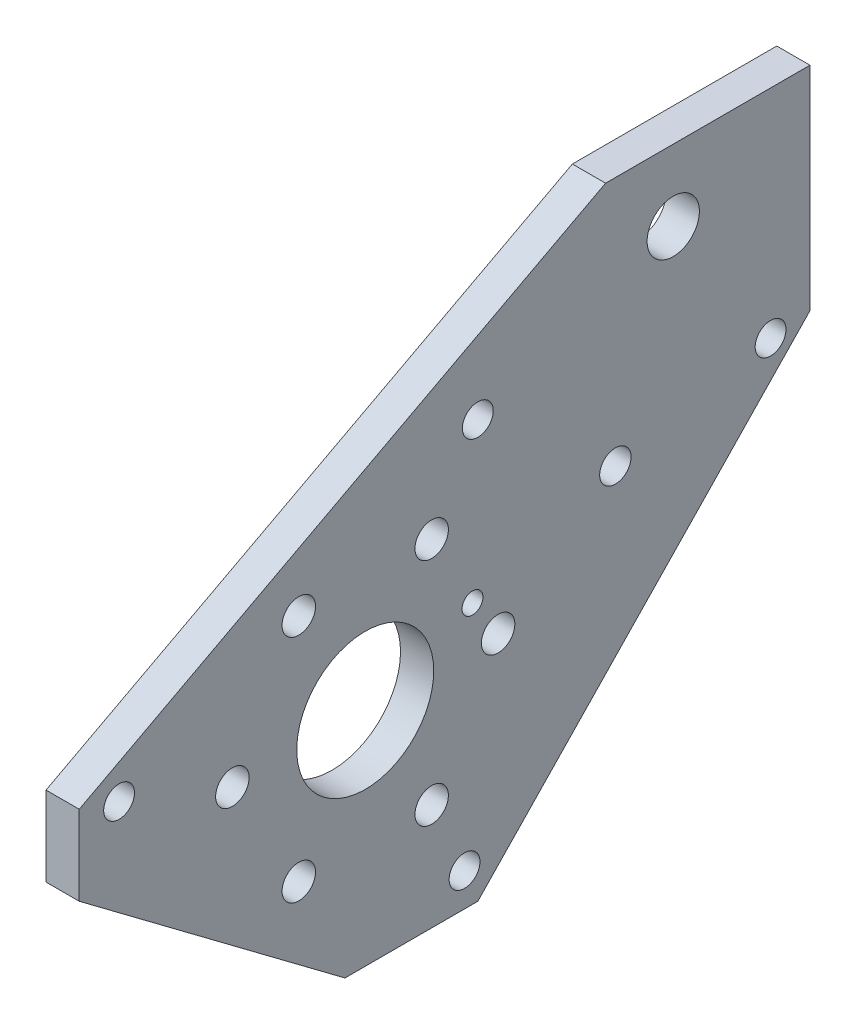
SolidWorks part; units mm, degrees
ref_plane "Front Plane" through (0, 0, 0) normal (0, 0, 1) x (1, 0, 0)
ref_plane "Top Plane" through (0, 0, 0) normal (0, 1, 0) x (1, 0, 0)
ref_plane "Right Plane" through (0, 0, 0) normal (1, 0, 0) x (0, 0, -1)
sketch "Sketch1" plane through (0, 0, 0) normal (1, 0, 0) x (0, 0, -1)
  line L1 (0, 0) -> (69.85, 0)
  line L2 (0, 0) -> (0, 53.34)
  line L3 (0, 53.34) -> (69.85, 53.34)
  line L4 (69.85, 0) -> (69.85, 53.34)
  dimension "D1" = 53.34
  dimension "D2" = 69.85
extrude "Boss-Extrude1" add sketch "Sketch1" along normal blind 3.175
hole_wizard "1/2 Clearance Hole1" positions "Sketch3" profile "Sketch2" hole size "1/2" standard "ANSI Inch"
sketch "Sketch3" plane through (3.175, 0, 0) normal (1, 0, 0) x (0, 0, -1)
  line L0 (0, 0) -> (69.85, 0) construction
  line L1 (0, 53.34) -> (0, 0) construction
  point P0 (27.3378, 21.1869)
  point P3 (34.925, 0)
  dimension "D1" = 21.1869
  dimension "D2" = 27.3378
sketch "Sketch2" plane through (3.175, 21.1869, -27.3378) normal (0, 1, 0) x (0, 0, -1)
  line L0 (0, 0) -> (0, 29.3345)
  line L1 (0, 29.3345) -> (6.5481, 25.4)
  line L2 (6.5481, 25.4) -> (6.5481, 0)
  line L5 (6.5481, 0) -> (0, 0)
  line L10 (0, 29.3345) -> (-6.5481, 25.4) construction
  line L11 (0, -6.35) -> (0, 107.95) construction
  dimension "Hole Dia." = 13.0962
  dimension "Hole Depth" = 25.4
  dimension "Drill Angle" = 118
hole_wizard "M3 Clearance Hole1" positions "Sketch5" profile "Sketch4" hole size "M3" standard "ANSI Metric"
sketch "Sketch5" plane through (0, 0, 0) normal (-1, 0, 0) x (0, 0, 1)
  line L11 (-27.3378, 21.1869) -> (-40.0378, 21.1869) construction
  line L12 (-27.3378, 21.1869) -> (-33.6878, 32.1855) construction
  line L13 (-27.3378, 21.1869) -> (-20.9878, 32.1855) construction
  line L14 (-27.3378, 21.1869) -> (-14.6378, 21.1869) construction
  line L15 (-27.3378, 21.1869) -> (-20.9878, 10.1884) construction
  line L16 (-27.3378, 21.1869) -> (-33.6878, 10.1884) construction
  point P55 (-40.0378, 21.1869)
  point P66 (-33.6878, 32.1855)
  point P67 (-20.9878, 32.1855)
  point P68 (-14.6378, 21.1869)
  point P69 (-20.9878, 10.1884)
  point P70 (-33.6878, 10.1884)
  point P71 (-27.3378, 21.1869)
  dimension "D1" = 12.7
  dimension "D2" = 6
sketch "Sketch4" plane through (0, 21.1869, -40.0378) normal (0, 1, 0) x (0, 0, 1)
  line L0 (0, 0) -> (0, 26.3614)
  line L1 (0, 26.3614) -> (1.6, 25.4)
  line L2 (1.6, 25.4) -> (1.6, 0)
  line L5 (1.6, 0) -> (0, 0)
  line L10 (0, 26.3614) -> (-1.6, 25.4) construction
  line L11 (0, -6.35) -> (0, 107.95) construction
  dimension "Hole Dia." = 3.2
  dimension "Hole Depth" = 25.4
  dimension "Drill Angle" = 118
hole_wizard "Ø2.0mm Clearance Dowel Hole1" positions "Sketch7" profile "Sketch6" hole size "Ø2.0" standard "ANSI Metric"
sketch "Sketch7" plane through (3.175, 0, 0) normal (1, 0, 0) x (0, 0, -1)
  line L0 (0, 53.34) -> (0, 0) construction
  line L1 (0, 0) -> (69.85, 0) construction
  point P0 (37.5906, 24.9513)
  dimension "D1" = 37.5906
  dimension "D2" = 24.9513
sketch "Sketch6" plane through (3.175, 24.9513, -37.5906) normal (0, 1, 0) x (0, 0, -1)
  line L0 (0, 0) -> (0, 26.0009)
  line L1 (0, 26.0009) -> (1, 25.4)
  line L2 (1, 25.4) -> (1, 0)
  line L5 (1, 0) -> (0, 0)
  line L10 (0, 26.0009) -> (-1, 25.4) construction
  line L11 (0, -6.35) -> (0, 107.95) construction
  dimension "Hole Dia." = 2
  dimension "Hole Depth" = 25.4
  dimension "Drill Angle" = 118
hole_wizard "Ø3.0mm Clearance Dowel Hole1" positions "Sketch9" profile "Sketch8" hole size "Ø3.0" standard "ANSI Metric"
sketch "Sketch9" plane through (3.175, 0, 0) normal (1, 0, 0) x (0, 0, -1)
  line L0 (0, 53.34) -> (0, 0) construction
  line L1 (0, 0) -> (69.85, 0) construction
  point P0 (51.2475, 29.4626)
  dimension "D1" = 51.2475
  dimension "D2" = 29.4626
sketch "Sketch8" plane through (3.175, 29.4626, -51.2475) normal (0, 1, 0) x (0, 0, -1)
  line L0 (0, 0) -> (0, 26.3013)
  line L1 (0, 26.3013) -> (1.5, 25.4)
  line L2 (1.5, 25.4) -> (1.5, 0)
  line L5 (1.5, 0) -> (0, 0)
  line L10 (0, 26.3013) -> (-1.5, 25.4) construction
  line L11 (0, -6.35) -> (0, 107.95) construction
  dimension "Hole Dia." = 3
  dimension "Hole Depth" = 25.4
  dimension "Drill Angle" = 118
hole_wizard "Ø5.0mm Clearance Dowel Hole1" positions "Sketch11" profile "Sketch10" hole size "Ø5.0" standard "ANSI Metric"
sketch "Sketch11" plane through (3.175, 0, 0) normal (1, 0, 0) x (0, 0, -1)
  line L0 (0, 0) -> (69.85, 0) construction
  line L1 (0, 53.34) -> (0, 0) construction
  point P0 (56.7803, 46.5335)
  dimension "D1" = 46.5335
  dimension "D2" = 56.7803
sketch "Sketch10" plane through (3.175, 46.5335, -56.7803) normal (0, 1, 0) x (0, 0, -1)
  line L0 (0, 0) -> (0, 26.9022)
  line L1 (0, 26.9022) -> (2.5, 25.4)
  line L2 (2.5, 25.4) -> (2.5, 0)
  line L5 (2.5, 0) -> (0, 0)
  line L10 (0, 26.9022) -> (-2.5, 25.4) construction
  line L11 (0, -6.35) -> (0, 107.95) construction
  dimension "Hole Dia." = 5
  dimension "Hole Depth" = 25.4
  dimension "Drill Angle" = 118
sketch "Sketch12" plane through (3.175, 0, 0) normal (1, 0, 0) x (0, 0, -1)
  line L0 (0, 53.34) -> (50.3135, 53.34)
  line L1 (69.85, 53.34) -> (0, 53.34) construction
  line L2 (50.3135, 53.34) -> (0, 26.67)
  line L3 (0, 53.34) -> (0, 0) construction
  line L4 (0, 26.67) -> (0, 53.34)
  line L5 (69.85, 0) -> (38.1, 0)
  line L6 (25.4, 0) -> (0, 19.05)
  line L7 (0, 0) -> (69.85, 0) construction
  line L8 (69.85, 0) -> (69.85, 53.34) construction
  line L9 (69.85, 33.02) -> (69.85, 0)
  line L10 (38.1, 0) -> (69.85, 33.02)
  line L11 (0, 19.05) -> (0, 0)
  line L12 (0, 0) -> (25.4, 0)
  dimension "D1" = 33.02
  dimension "D2" = 31.75
  dimension "D3" = 25.4
  dimension "D4" = 19.05
extrude "Cut-Extrude1" cut sketch "Sketch12" against normal through all
hole_wizard "#4 Clearance Hole1" positions "Sketch14" profile "Sketch13" hole size "#4" standard "Progressive"
sketch "Sketch14" plane through (3.175, 0, 0) normal (1, 0, 0) x (0, 0, -1)
  line L0 (0, 26.67) -> (0, 19.05) construction
  line L1 (25.4, 0) -> (38.1, 0) construction
  point P0 (3.81, 25.4)
  point P7 (36.83, 3.175)
  point P10 (66.0867, 32.6229)
  point P14 (38.1, 39.878)
  dimension "D1" = 3.81
  dimension "D2" = 25.4
  dimension "D3" = 36.83
  dimension "D4" = 3.175
  dimension "D5" = 32.6229
  dimension "D6" = 66.0867
  dimension "D7" = 38.1
  dimension "D8" = 39.878
sketch "Sketch13" plane through (3.175, 25.4, -3.81) normal (0, 1, 0) x (0, 0, -1)
  line L0 (0, 0) -> (0, 4.0602)
  line L1 (0, 4.0602) -> (1.4732, 3.175)
  line L2 (1.4732, 3.175) -> (1.4732, 0)
  line L5 (1.4732, 0) -> (0, 0)
  line L10 (0, 4.0602) -> (-1.4732, 3.175) construction
  line L11 (0, -6.35) -> (0, 107.95) construction
  dimension "Hole Dia." = 2.9464
  dimension "Hole Depth" = 3.175
  dimension "Drill Angle" = 118
fillet "Fillet1" [suppressed] radius 2.54
